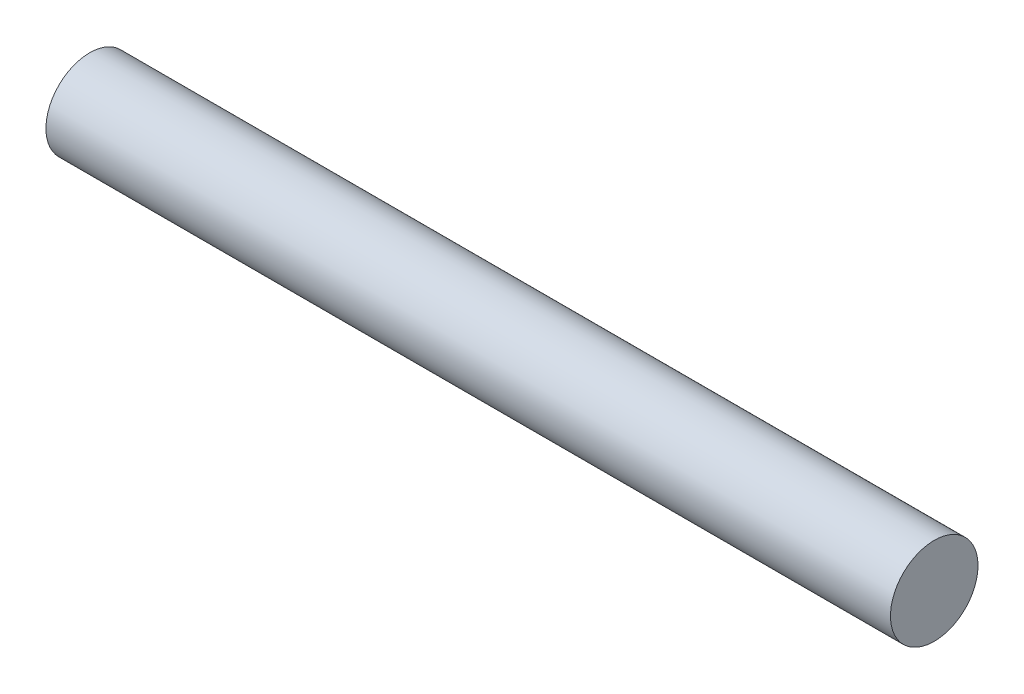
SolidWorks part; units mm, degrees
ref_plane "前视基准面" through (0, 0, 0) normal (0, 0, 1) x (1, 0, 0)
ref_plane "上视基准面" through (0, 0, 0) normal (0, 1, 0) x (1, 0, 0)
ref_plane "右视基准面" through (0, 0, 0) normal (1, 0, 0) x (0, 0, -1)
sketch "草图1" plane through (0, 0, 0) normal (1, 0, 0) x (0, 0, -1)
  circle A0 centre (0, 0) radius 5.7
  dimension "D2" = 11.4
extrude "凸台-拉伸1" add sketch "草图1" along normal blind 110 contours A0
